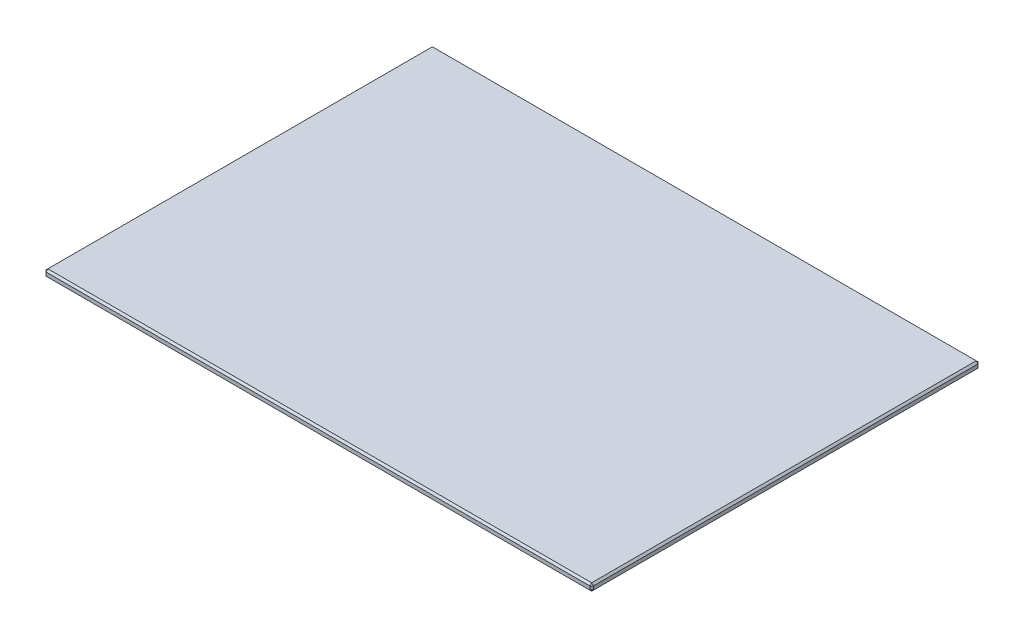
SolidWorks part; units mm, degrees
material "Glass"
ref_plane "Alzado" through (0, 0, 0) normal (0, 0, 1) x (1, 0, 0)
ref_plane "Planta" through (0, 0, 0) normal (0, 1, 0) x (1, 0, 0)
ref_plane "Vista lateral" through (0, 0, 0) normal (1, 0, 0) x (0, 0, -1)
sketch "Croquis1" plane through (0, 0, 0) normal (0, 1, 0) x (1, 0, 0)
  line L0 (-149.5, 106) -> (149.5, -106) construction
  line L1 (-149.5, -106) -> (149.5, -106)
  line L2 (-149.5, -106) -> (-149.5, 106)
  line L3 (-149.5, 106) -> (149.5, 106)
  line L4 (149.5, -106) -> (149.5, 106)
  dimension "D1" = 212
  dimension "D2" = 299
extrude "Saliente-Extruir1" add sketch "Croquis1" along normal blind 4
chamfer "Chaflán1" distance 1 angle 45 12 edges at (0, 0, 106) (149.5, 0, 0) (0, 0, -106) (-149.5, 0, 0) (0, 4, -106) (149.5, 4, 0) (0, 4, 106) (-149.5, 4, 0) (149.5, 2, -106) (149.5, 2, 106) (-149.5, 2, -106) (-149.5, 2, 106)
